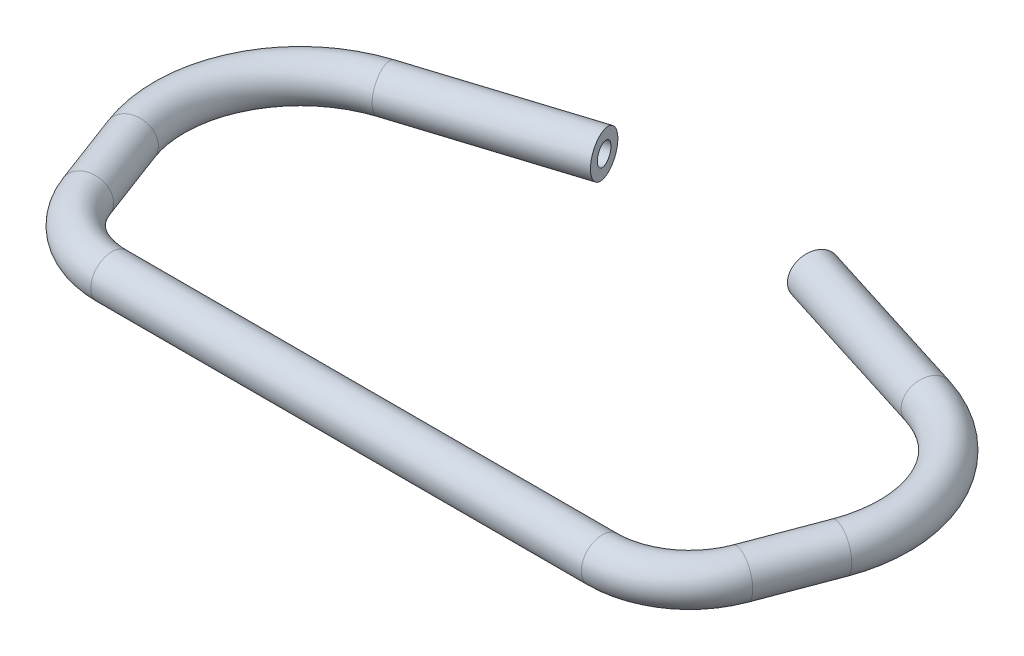
SolidWorks part; units mm, degrees
material "1060 Alloy"
ref_plane "Plano frontal" through (0, 0, 0) normal (0, 0, 1) x (1, 0, 0)
ref_plane "Plano superior" through (0, 0, 0) normal (0, 1, 0) x (1, 0, 0)
ref_plane "Plano direito" through (0, 0, 0) normal (1, 0, 0) x (0, 0, -1)
sketch "Sketch2" plane through (0, 0, 0) normal (0, 1, 0) x (1, 0, 0)
  line L7 (140.394, 0) -> (-140.394, 0)
  line L15 (187.1895, 32.3881) -> (175, 0) construction
  line L16 (-187.1895, 32.3881) -> (-202.6933, 73.5821)
  line L17 (-187.1895, 32.3881) -> (-175, 0) construction
  line L18 (-155.0529, 171.5288) -> (-60, 201.4988)
  line L19 (0, -55) -> (0, 55) construction
  line L20 (155.0529, 171.5288) -> (60, 201.4988)
  line L21 (-140.394, 0) -> (-175, 0) construction
  line L22 (187.1895, 32.3881) -> (202.6933, 73.5821)
  line L23 (140.394, 0) -> (175, 0) construction
  arc A0 (-202.6933, 73.5821) -> (-155.0529, 171.5288) centre (-132.5, 100) cw
  arc A3 (202.6933, 73.5821) -> (155.0529, 171.5288) centre (132.5, 100) ccw
  arc A5 (-187.1895, 32.3881) -> (-140.394, 0) centre (-140.394, 50) ccw
  arc A6 (187.1895, 32.3881) -> (140.394, 0) centre (140.394, 50) cw
  point P0 (-187.1895, 32.3881)
  point P8 (0, 0)
  point P18 (-459.9821, 321.7688)
  dimension "D1" = 350
  dimension "D2" = 120
  dimension "D3" = 75
  dimension "D4" = 100
  dimension "D5" = 265
  dimension "D6" = 145
  dimension "D7" = 42.5
  dimension "D8" = 50
sketch "Sketch3" plane through (0, 0, 0) normal (1, 0, 0) x (0, 0, -1)
  circle A0 centre (0, 0) radius 12
  circle A1 centre (0, 0) radius 6
  dimension "D1" = 24
  dimension "D2" = 12
sweep "Sweep7" add profiles "Sketch3" path "Sketch2"
